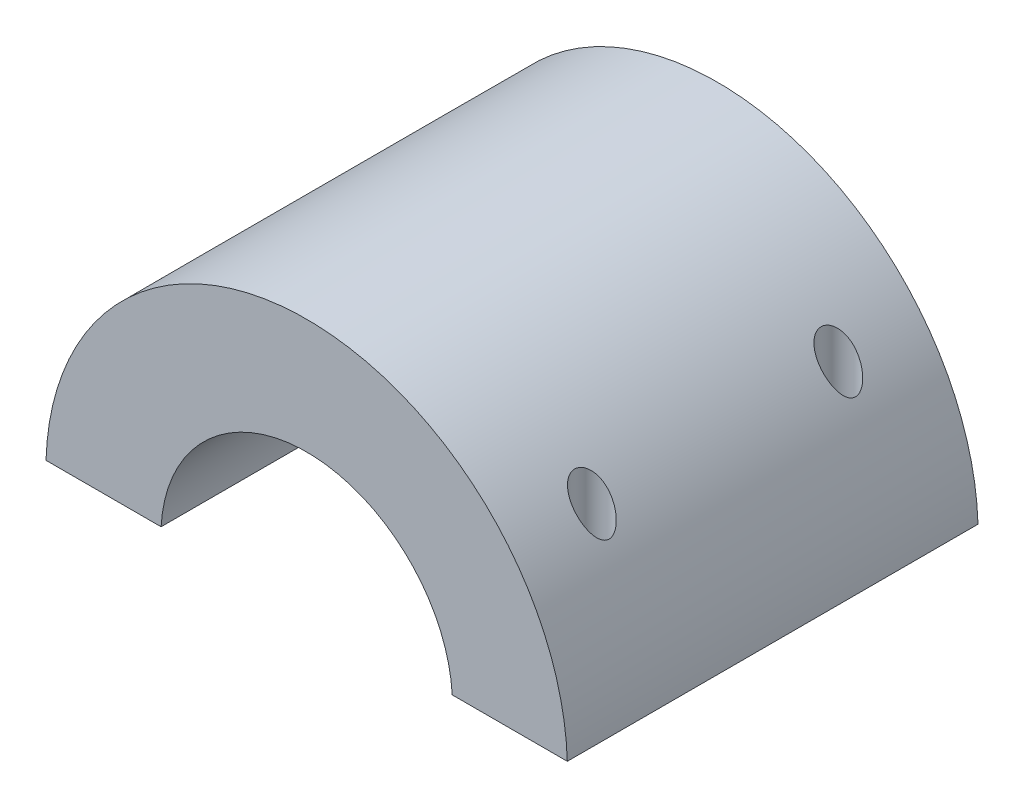
SolidWorks part; units mm, degrees
ref_plane "Front" through (0, 0, 0) normal (0, 0, 1) x (1, 0, 0)
ref_plane "Top" through (0, 0, 0) normal (0, 1, 0) x (1, 0, 0)
ref_plane "Right" through (0, 0, 0) normal (1, 0, 0) x (0, 0, -1)
sketch "Sketch1" plane through (0, 0, 0) normal (0, 0, 1) x (1, 0, 0)
  line L0 (-31.75, 0) -> (31.75, 0) construction
  line L1 (-31.7342, 1) -> (-17.7218, 1)
  line L2 (-31.75, 1) -> (31.75, 1) construction
  line L3 (17.7218, 1) -> (31.7342, 1)
  arc A0 (31.7342, 1) -> (-31.7342, 1) centre (0, 0) ccw
  arc A1 (17.7218, 1) -> (-17.7218, 1) centre (0, 0) ccw
  dimension "D1" = 35.5
  dimension "D2" = 63.5
  dimension "D3" = 1
extrude "Boss-Extrude1" add sketch "Sketch1" along normal blind 50
sketch "Sketch2" plane through (0, 1, 0) normal (0, -1, 0) x (-1, 0, 0)
  line L0 (24.728, -50) -> (24.728, 0) construction
  line L1 (31.7342, -50) -> (17.7218, -50) construction
  line L2 (31.7342, 0) -> (17.7218, 0) construction
  line L3 (-24.728, -50) -> (-24.728, 0) construction
  line L4 (-17.7218, -50) -> (-31.7342, -50) construction
  line L5 (-17.7218, 0) -> (-31.7342, 0) construction
  line L6 (0, -50) -> (0, 0) construction
  line L7 (-17.7218, -50) -> (17.7218, -50) construction
  circle A0 centre (24.728, -40) radius 1
  circle A1 centre (24.728, -10) radius 1
  circle A2 centre (-24.728, -10) radius 1
  circle A3 centre (-24.728, -40) radius 1
  dimension "D1" = 10
  dimension "D2" = 10
  dimension "D3" = 2
hole_wizard "Tap Drill for M5x0.8 Tap1" positions "3DSketch1" profile "Sketch3" hole size "M5x0.8" standard "ANSI Metric" end condition up to next
sketch3d "3DSketch1"
  point P0 (-24.728, 1, 40)
  point P3 (-24.728, 1, 10)
  point P6 (24.728, 1, 40)
  point P9 (24.728, 1, 10)
sketch "Sketch3" plane through (-24.728, 1, 40) normal (1, 0, 0) x (0, 0, -1)
  line L0 (0, 0) -> (0, 18.9145)
  line L1 (0, 18.9145) -> (2.1, 18.9145)
  line L2 (2.1, 18.9145) -> (2.1, 0)
  line L5 (2.1, 0) -> (0, 0)
  line L11 (0, -6.35) -> (0, 107.95) construction
  dimension "Thru Hole Dia." = 4.2
  dimension "Thru Hole Depth" = 18.9145
